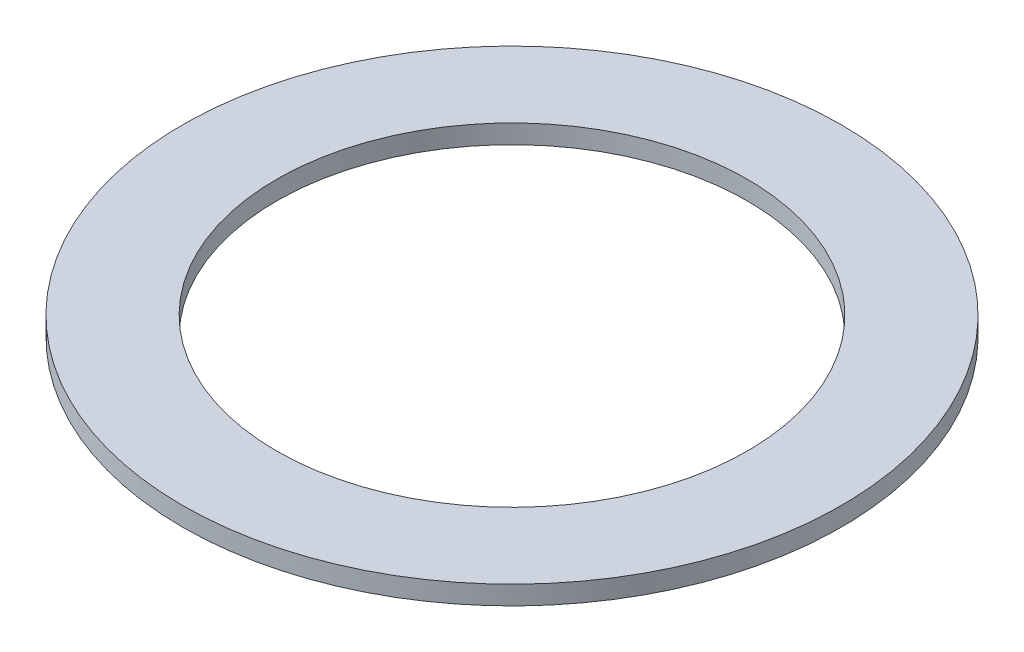
SolidWorks part; units mm, degrees
ref_plane "Front" through (0, 0, 0) normal (0, 0, 1) x (1, 0, 0)
ref_plane "Top" through (0, 0, 0) normal (0, 1, 0) x (1, 0, 0)
ref_plane "Right" through (0, 0, 0) normal (1, 0, 0) x (0, 0, -1)
sketch "Sketch1" plane through (0, 0, 0) normal (1, 0, 0) x (0, 0, -1)
  line L0 (0, 12.3439) -> (0, 0) construction
  line L1 (0, 0) -> (8.5784, 0) construction
  line L3 (2.5, 0.1) -> (3.5, 0.1)
  line L4 (2.5, 0.1) -> (2.5, -0.1)
  line L5 (2.5, -0.1) -> (3.5, -0.1)
  line L6 (3.5, 0.1) -> (3.5, -0.1)
  dimension "D1" = 5
  dimension "D2" = 7
  dimension "D3" = 0.2
revolve "Revolve1" add sketch "Sketch1" angle 360 about L0
